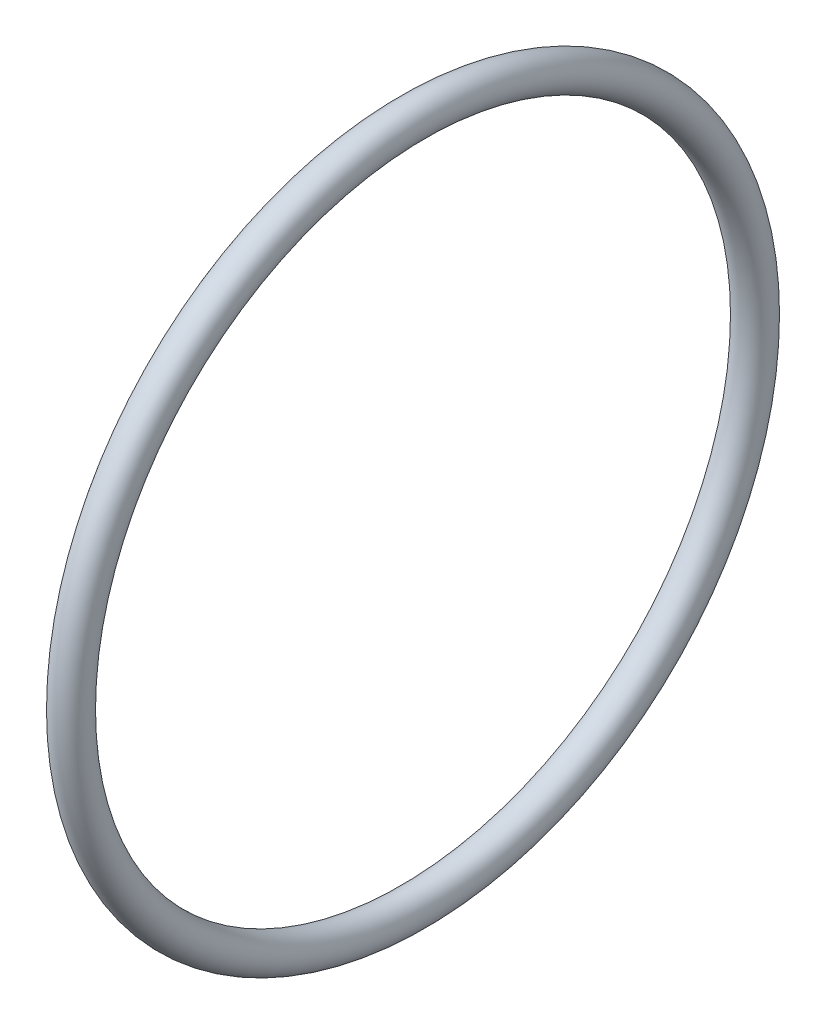
SolidWorks part; units mm, degrees
ref_plane "Piano frontale" through (0, 0, 0) normal (0, 0, 1) x (1, 0, 0)
ref_plane "Piano superiore" through (0, 0, 0) normal (0, 1, 0) x (1, 0, 0)
ref_plane "Piano destro" through (0, 0, 0) normal (1, 0, 0) x (0, 0, -1)
sketch "Schizzo2" plane through (0, 0, 0) normal (0, 0, 1) x (1, 0, 0)
  circle A0 centre (0, 19.715) radius 1
  dimension "D1" = 2
  dimension "D2" = 19.715
ref_axis "Asse1" through (-1.1, 0, 0) along (1, 0, 0)
revolve "Rivoluzione1" add sketch "Schizzo2" angle 360 about axis through (-1.1, 0, 0) along (1, 0, 0)
